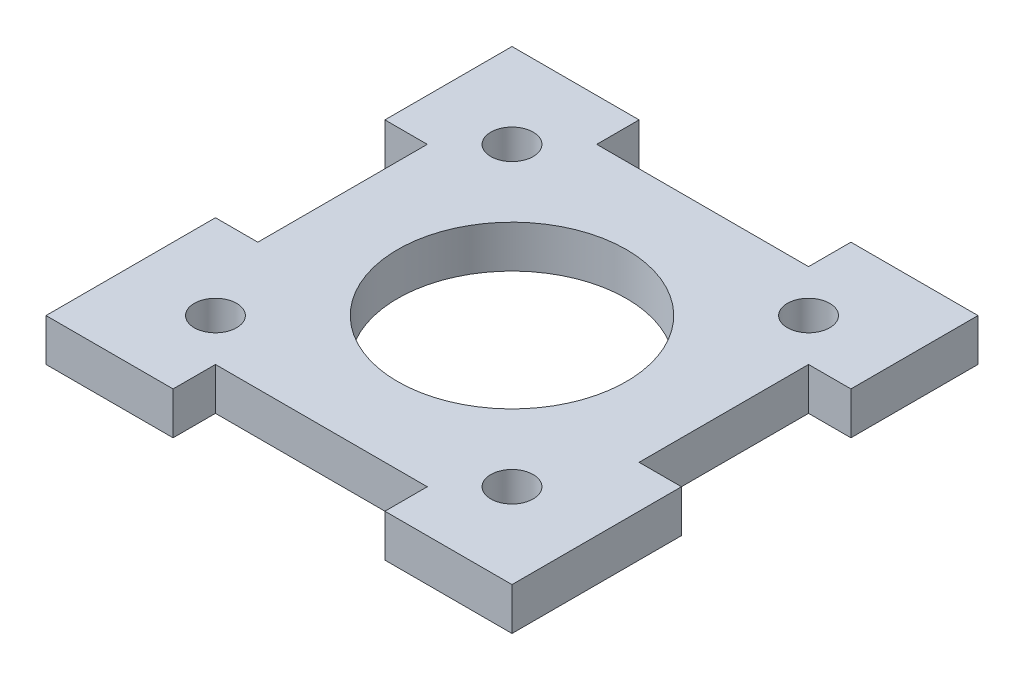
SolidWorks part; units mm, degrees
ref_plane "Plan de face" through (0, 0, 0) normal (0, 0, 1) x (1, 0, 0)
ref_plane "Plan de dessus" through (0, 0, 0) normal (0, 1, 0) x (1, 0, 0)
ref_plane "Plan de droite" through (0, 0, 0) normal (1, 0, 0) x (0, 0, -1)
sketch "Esquisse1" plane through (0, 0, 0) normal (0, 1, 0) x (1, 0, 0)
  line L0 (-12.5, 27.5) -> (-12.5, 22.5)
  line L1 (-27.5, 27.5) -> (-12.5, 27.5)
  line L2 (-27.5, 27.5) -> (-27.5, 12.5)
  line L3 (-27.5, -27.5) -> (-12.5, -27.5)
  line L4 (27.5, 27.5) -> (27.5, 12.5)
  line L5 (-27.5, 27.5) -> (27.5, -27.5) construction
  line L6 (-27.5, -27.5) -> (27.5, 27.5) construction
  line L7 (12.5, 27.5) -> (12.5, 22.5)
  line L8 (12.5, 22.5) -> (-12.5, 22.5)
  line L9 (25, 0) -> (-27.3973, 0) construction
  line L10 (-12.5, -27.5) -> (-12.5, -22.5)
  line L11 (12.5, -27.5) -> (12.5, -22.5)
  line L12 (12.5, -22.5) -> (-12.5, -22.5)
  line L13 (0, 26.9977) -> (0, -29.395) construction
  line L14 (27.5, 12.5) -> (22.5, 12.5)
  line L15 (27.5, -7.5) -> (22.5, -7.5)
  line L16 (22.5, -7.5) -> (22.5, 12.5)
  line L17 (-27.5, -7.5) -> (-22.5, -7.5)
  line L18 (-22.5, -7.5) -> (-22.5, 12.5)
  line L19 (-27.5, 12.5) -> (-22.5, 12.5)
  line L20 (27.5, -7.5) -> (27.5, -27.5)
  line L21 (-27.5, -7.5) -> (-27.5, -27.5)
  line L22 (12.5, 27.5) -> (27.5, 27.5)
  line L23 (12.5, -27.5) -> (27.5, -27.5)
  circle A0 centre (17.5, 17.5) radius 2.5
  circle A1 centre (-17.5, 17.5) radius 2.5
  circle A2 centre (-17.5, -17.5) radius 2.5
  circle A3 centre (17.5, -17.5) radius 2.5
  circle A4 centre (0, 0) radius 13.5
  point P0 (0, 0)
  dimension "D4" = 5
  dimension "D8" = 27
  dimension "D1" = 55
  dimension "D2" = 55
  dimension "D3" = 5
  dimension "D5" = 10
  dimension "D6" = 15
  dimension "D7" = 15
  dimension "D9" = 5
  dimension "D10" = 20
  dimension "D11" = 15
extrude "Boss.-Extru.1" add sketch "Esquisse1" along normal blind 5
